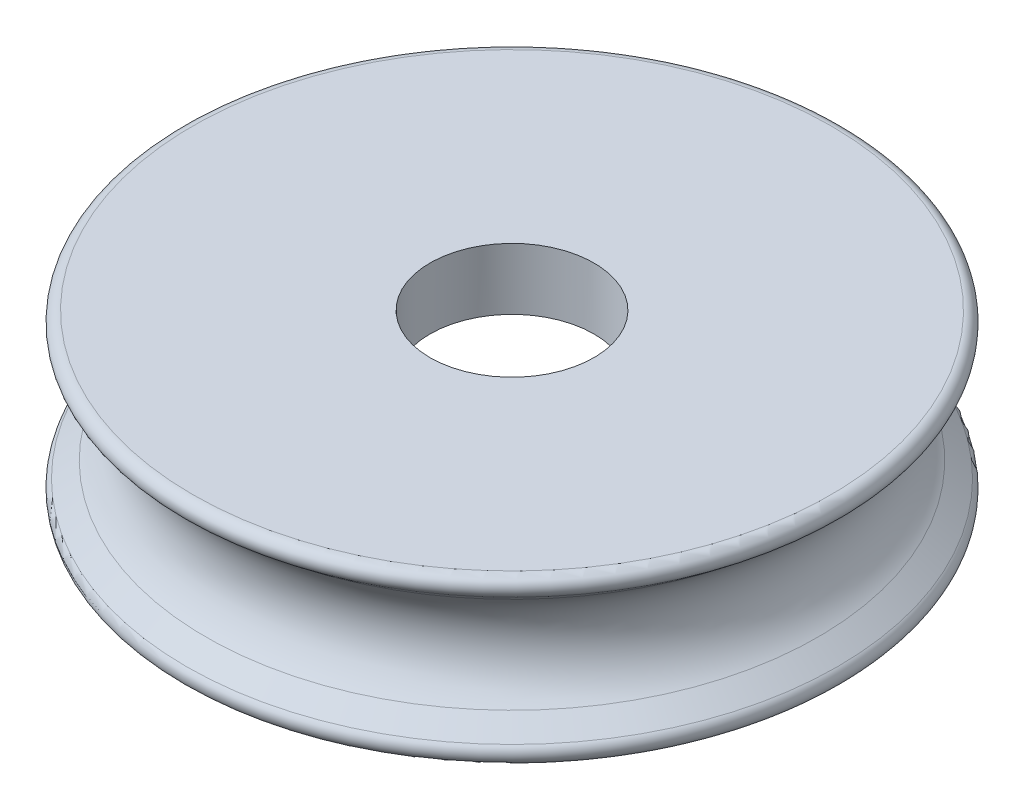
SolidWorks part; units mm, degrees
ref_plane "Спереди" through (0, 0, 0) normal (0, 0, 1) x (1, 0, 0)
ref_plane "Сверху" through (0, 0, 0) normal (0, 1, 0) x (1, 0, 0)
ref_plane "Справа" through (0, 0, 0) normal (1, 0, 0) x (0, 0, -1)
sketch "Эскиз1" plane through (0, 0, 0) normal (0, 1, 0) x (1, 0, 0)
  circle A1 centre (0, 0) radius 17
extrude "Вытянуть1" add sketch "Эскиз1" along normal blind 8
sketch "Эскиз2" plane through (0, 0, 0) normal (0, -1, 0) x (1, 0, 0)
  circle A0 centre (0, 0) radius 12
extrude "Вытянуть2" cut sketch "Эскиз2" against normal blind 5
sketch "Эскиз4" plane through (0, 0, 0) normal (1, 0, 0) x (0, 0, -1)
  line L0 (17, 4) -> (28.0104, 4) construction
  line L1 (-17, 0) -> (17, 0) construction
  line L2 (17, 8) -> (14.9283, 6.3426)
  line L3 (0, 11) -> (0, 26.4794) construction
  line L4 (14.9283, 1.6574) -> (17, 0)
  line L5 (17, 0) -> (17, 8)
  arc A0 (14.9283, 1.6574) -> (14.9283, 6.3426) centre (16.8023, 4) cw
  point P8 (12, 4)
  dimension "D2" = 3
  dimension "D3" = 4
  dimension "D1" = 5
revolve "Вырез-Повернуть1" cut sketch "Эскиз4" angle 360 about L3
fillet "Скругление1" radius 0.5 2 edges at (0, 8, -17) (0, 0, -17)
sketch "Эскиз5" plane through (0, 8, 0) normal (0, 1, 0) x (1, 0, 0)
  circle A0 centre (0, 0) radius 4
extrude "Вытянуть3" cut sketch "Эскиз5" against normal through all
